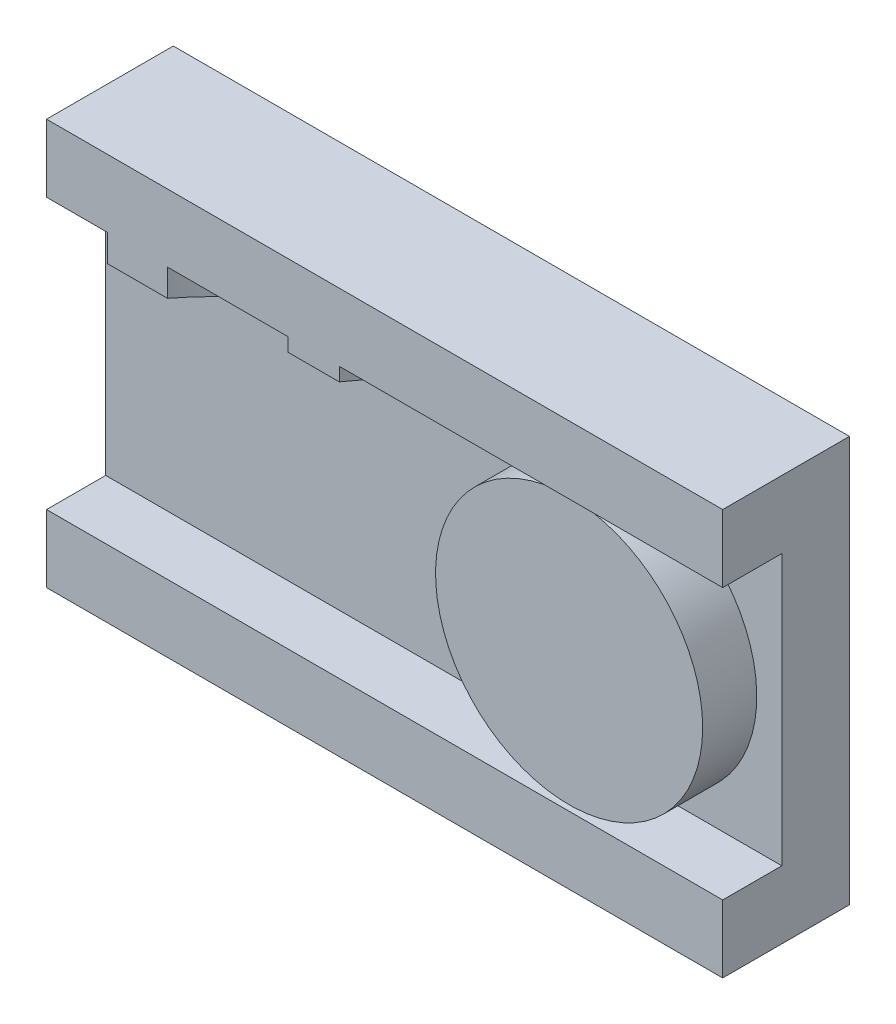
SolidWorks part; units mm, degrees
ref_plane "Front Plane" through (0, 0, 0) normal (0, 0, 1) x (1, 0, 0)
ref_plane "Top Plane" through (0, 0, 0) normal (0, 1, 0) x (1, 0, 0)
ref_plane "Right Plane" through (0, 0, 0) normal (1, 0, 0) x (0, 0, -1)
sketch "Sketch1" plane through (0, 0, 0) normal (1, 0, 0) x (0, 0, -1)
  line L1 (-5.5357, -1.4732) -> (14.4643, -1.4732)
  line L2 (-5.5357, -1.4732) -> (-5.5357, -6.4732)
  line L3 (-5.5357, -6.4732) -> (14.4643, -6.4732)
  line L4 (14.4643, -1.4732) -> (14.4643, -6.4732)
  line L9 (14.4643, 18.5268) -> (-5.5357, 18.5268)
  line L10 (14.4643, 18.5268) -> (14.4643, 23.5268)
  line L11 (14.4643, 23.5268) -> (-5.5357, 23.5268)
  line L12 (-5.5357, 18.5268) -> (-5.5357, 23.5268)
  line L13 (9.4643, 18.5268) -> (14.4643, 18.5268)
  line L14 (9.4643, 18.5268) -> (9.4643, -1.4732)
  line L15 (9.4643, -1.4732) -> (14.4643, -1.4732)
  line L16 (14.4643, 18.5268) -> (14.4643, -1.4732)
  dimension "D1" = 5
  dimension "D2" = 5
  dimension "D3" = 20
  dimension "D4" = 20
  dimension "D5" = 5
  dimension "D6" = 20
extrude "Boss-Extrude2" add sketch "Sketch1" along normal blind 50 contours L16 L9 L14 L1 | L12 L9 L10 L11 | L4 L1 L2 L3
sketch "Sketch2" plane through (0, 18.5268, 0) normal (0, -1, 0) x (1, 0, 0)
  line L4 (4.5158, -9.4643) -> (4.5158, 5.5357)
  line L6 (50, -9.4643) -> (0, -9.4643) construction
  line L7 (50, 5.5357) -> (0, 5.5357) construction
  line L8 (4.5158, -9.4643) -> (13.489, -9.4643)
  spline S0 degree 2 poles (4.5158, 5.5357) (5.8488, -3.8061) (13.489, -9.4643) knots 0 0 0 1 1 1
extrude "Boss-Extrude3" add sketch "Sketch2" along normal blind 2
sketch "Sketch4" plane through (0, 18.5268, 0) normal (0, -1, 0) x (1, 0, 0)
  line L0 (17.8655, -10.3178) -> (17.8655, 5.5357)
  line L1 (17.8655, -10.3178) -> (26.8388, -10.3178)
  line L2 (50, 5.5357) -> (4.5158, 5.5357) construction
  spline S0 degree 2 poles (17.8655, 5.5357) (18.7958, -4.3993) (26.8388, -10.3178) knots 0 0 0 1 1 1
  dimension "D1" = 0
extrude "Boss-Extrude4" add sketch "Sketch4" along normal blind 1
sketch "Sketch5" plane through (50, 0, 0) normal (1, 0, 0) x (0, 0, -1)
  line L0 (-5.5357, -6.4732) -> (14.4643, -6.4732) construction
  line L1 (-5.5357, 23.5268) -> (5.0918, 23.5268)
  line L2 (-5.5357, 23.5268) -> (-5.5357, -6.4732)
  line L3 (-5.5357, -6.4732) -> (5.0918, -6.4732)
  line L4 (5.0918, 23.5268) -> (5.0918, -6.4732)
extrude "Cut-Extrude1" cut sketch "Sketch5" against normal blind 410
sketch "Sketch6" plane through (0, 0, -9.4643) normal (0, 0, 1) x (1, 0, 0)
  circle A0 centre (38.2696, 8.4459) radius 9.8766
extrude "Boss-Extrude5" add sketch "Sketch6" along normal blind 4
